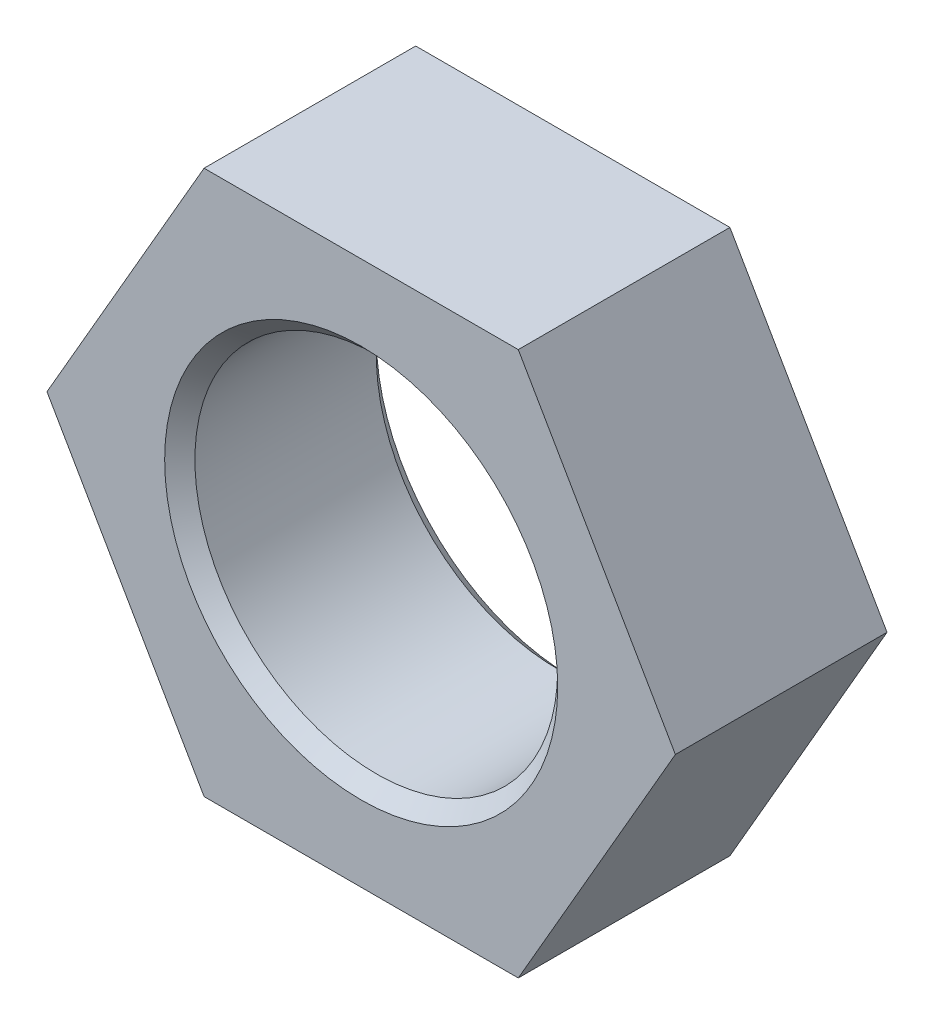
SolidWorks part; units mm, degrees
ref_plane "Ön Düzlem" through (0, 0, 0) normal (0, 0, 1) x (1, 0, 0)
ref_plane "Üst Düzlem" through (0, 0, 0) normal (0, 1, 0) x (1, 0, 0)
ref_plane "Sağ Düzlem" through (0, 0, 0) normal (1, 0, 0) x (0, 0, -1)
sketch "Çizim1" plane through (0, 0, 0) normal (0, 0, 1) x (1, 0, 0)
  line L1 (5.1962, 0) -> (2.5981, 4.5)
  line L2 (2.5981, 4.5) -> (-2.5981, 4.5)
  line L3 (-2.5981, 4.5) -> (-5.1962, 0)
  line L4 (-5.1962, 0) -> (-2.5981, -4.5)
  line L5 (-2.5981, -4.5) -> (2.5981, -4.5)
  line L6 (2.5981, -4.5) -> (5.1962, 0)
  circle A0 centre (0, 0) radius 3
  circle A1 centre (0, 0) radius 4.5 construction
  dimension "D1" = 6
  dimension "D2" = 4.5
extrude "Yükseklik-Ekstrüzyon1" add sketch "Çizim1" along normal blind 3.5
chamfer "Pah1" distance 0.25 angle 45 2 edges at (3, 0, 0) (3, 0, 3.5)
